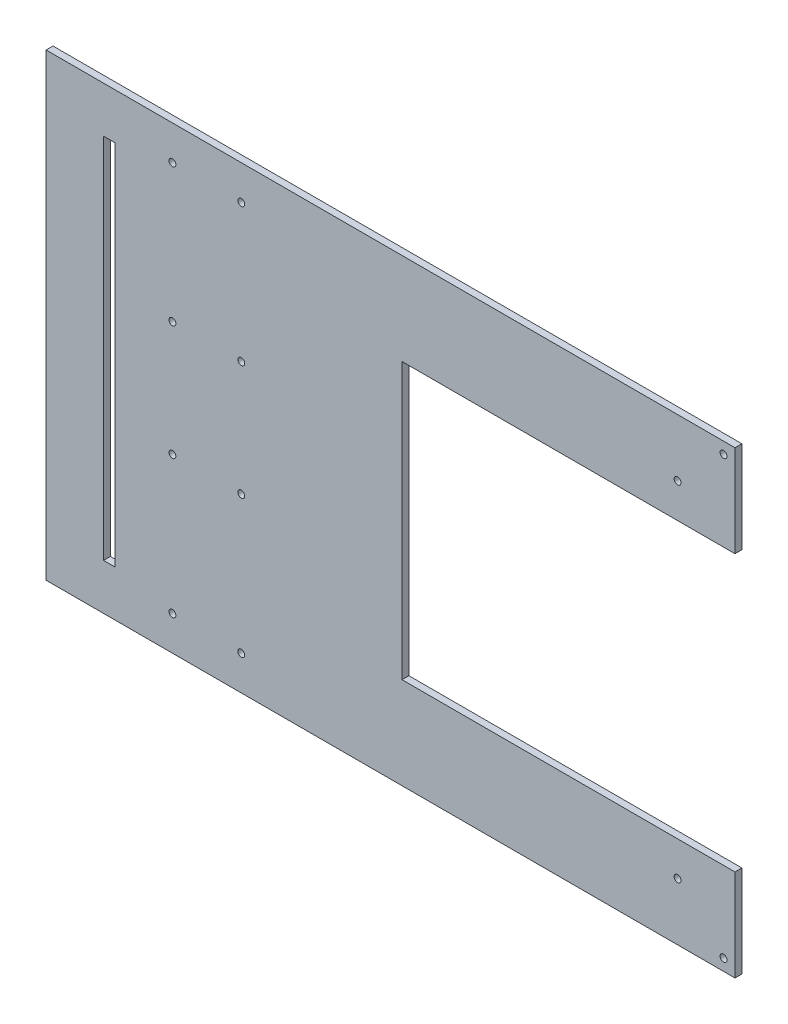
SolidWorks part; units mm, degrees
ref_plane "Front Plane" through (0, 0, 0) normal (0, 0, 1) x (1, 0, 0)
ref_plane "Top Plane" through (0, 0, 0) normal (0, 1, 0) x (1, 0, 0)
ref_plane "Right Plane" through (0, 0, 0) normal (1, 0, 0) x (0, 0, -1)
sketch "Sketch1" plane through (0, 0, 0) normal (0, 0, 1) x (1, 0, 0)
  line L1 (0, 0) -> (300, 0)
  line L2 (0, 0) -> (0, 200)
  line L3 (0, 200) -> (300, 200)
  line L4 (300, 0) -> (300, 200)
  dimension "D1" = 200
  dimension "D2" = 300
extrude "Boss-Extrude1" add sketch "Sketch1" along normal blind 3
sketch "Sketch2" plane through (0, 0, 0) normal (0, 0, 1) x (1, 0, 0)
  line L0 (300, 0) -> (300, 200) construction
  line L1 (300, 160) -> (155, 160)
  line L2 (300, 160) -> (300, 40)
  line L3 (300, 40) -> (155, 40)
  line L4 (155, 160) -> (155, 40)
  line L7 (0, 0) -> (300, 0) construction
  line L8 (300, 200) -> (0, 200) construction
  dimension "D1" = 40
  dimension "D2" = 40
  dimension "D3" = 145
extrude "Cut-Extrude1" cut sketch "Sketch2" along normal up to surface (3 mm away) contours L1 L4 L3 L2 up to face at (150, 100, 3)
sketch "Sketch3" plane through (0, 0, 0) normal (0, 0, 1) x (1, 0, 0)
  line L0 (300, 200) -> (0, 200) construction
  line L1 (25, 180) -> (30, 180)
  line L2 (25, 180) -> (25, 20)
  line L3 (25, 20) -> (30, 20)
  line L4 (30, 180) -> (30, 20)
  line L5 (0, 0) -> (300, 0) construction
  line L6 (0, 200) -> (0, 0) construction
  dimension "D1" = 20
  dimension "D2" = 20
  dimension "D3" = 25
  dimension "D4" = 5
extrude "Cut-Extrude2" cut sketch "Sketch3" along normal up to surface (3 mm away) up to face at (188.75, 100, 3)
hole_wizard "Ø3.0mm Dowel Hole1" positions "Sketch5" profile "Sketch6" hole size "Ø3.0" standard "ANSI Metric" end condition through all
sketch "Sketch5" plane through (0, 0, 0) normal (0, 0, -1) x (-1, 0, 0)
  line L0 (0, 200) -> (0, 0) construction
  line L1 (0, 0) -> (-300, 0) construction
  line L2 (-155, 100) -> (0, 100) construction
  line L3 (-155, 160) -> (-155, 40) construction
  line L4 (-300, 0) -> (-300, 40) construction
  point P8 (-85, 75)
  point P10 (-55, 75)
  point P12 (-55, 15)
  point P14 (-85, 15)
  point P16 (-295, 5)
  point P18 (-275, 25)
  point P36 (-85, 185)
  point P37 (-55, 185)
  point P38 (-55, 125)
  point P39 (-85, 125)
  point P42 (-275, 175)
  point P43 (-295, 195)
  dimension "D1" = 30
  dimension "D2" = 55
  dimension "D3" = 15
  dimension "D4" = 60
  dimension "D5" = 5
  dimension "D6" = 5
  dimension "D7" = 25
  dimension "D8" = 25
sketch "Sketch6" plane through (85, 75, 0) normal (1, 0, 0) x (0, 1, 0)
  line L0 (0, 0) -> (0, 3)
  line L1 (0, 3) -> (1.5, 3)
  line L2 (1.5, 3) -> (1.5, 0)
  line L5 (1.5, 0) -> (0, 0)
  line L11 (0, -6.35) -> (0, 107.95) construction
  dimension "Thru Hole Dia." = 3
  dimension "Thru Hole Depth" = 3
